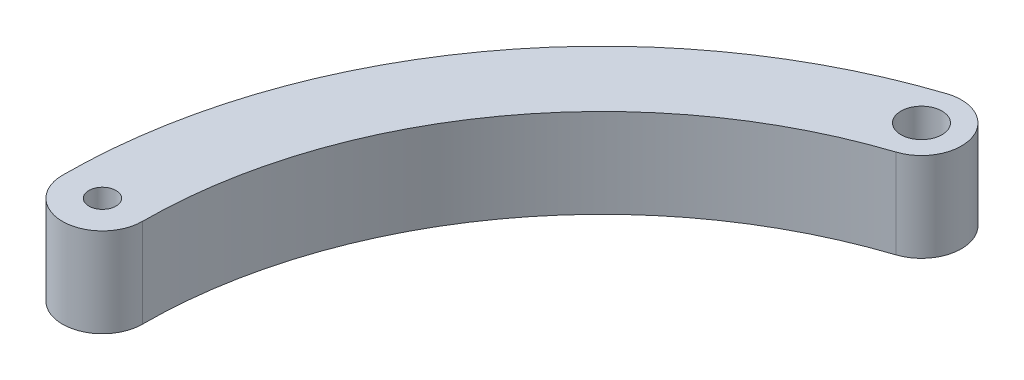
SolidWorks part; units mm, degrees
material "ABS"
ref_plane "Front Plane" through (0, 0, 0) normal (0, 0, 1) x (1, 0, 0)
ref_plane "Top Plane" through (0, 0, 0) normal (0, 1, 0) x (1, 0, 0)
ref_plane "Right Plane" through (0, 0, 0) normal (1, 0, 0) x (0, 0, -1)
sketch "Sketch1" plane through (0, 0, 0) normal (0, 1, 0) x (1, 0, 0)
  arc A2 (-33.5905, 0) -> (-10.4454, 31.9251) centre (0, 0) cw
  arc A3 (-39.4345, 0) -> (-12.2627, 37.4794) centre (0, 0) cw
  arc A4 (-10.4454, 31.9251) -> (-12.2627, 37.4794) centre (-11.3541, 34.7023) ccw
  arc A5 (-33.5905, 0) -> (-39.4345, 0) centre (-36.5125, 0) cw
  circle A6 centre (-36.5125, 0) radius 0.9922
  circle A7 centre (-11.3541, 34.7023) radius 1.5
  dimension "D3" = 1.9844
  dimension "D4" = 3
  dimension "D1" = 42.8625
  dimension "D2" = 36.5125
extrude "Boss-Extrude1" add sketch "Sketch1" along normal blind 6.51
